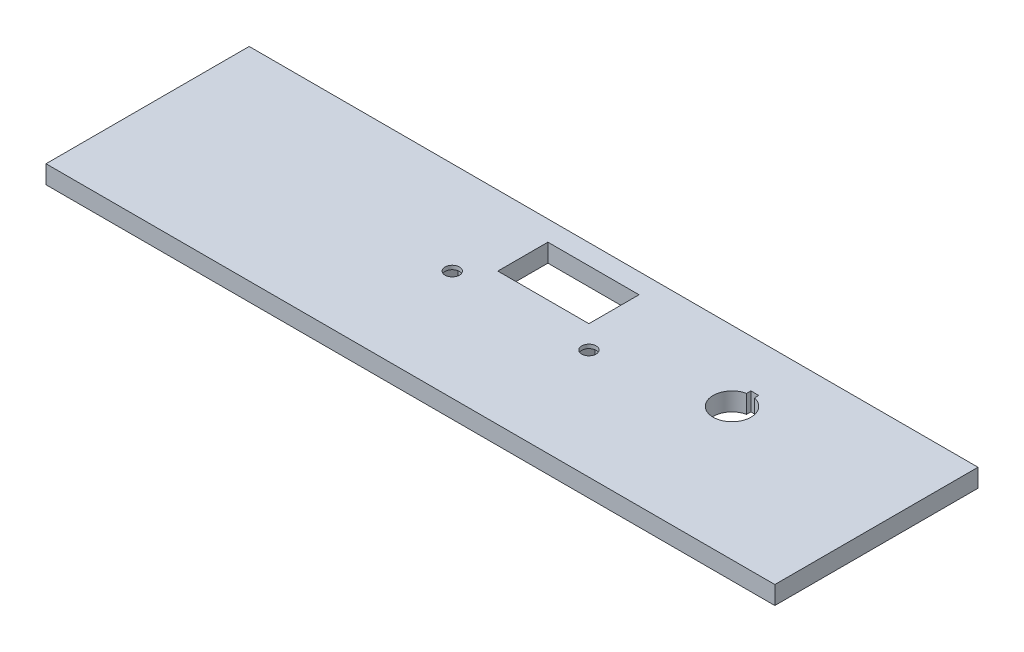
SolidWorks part; units mm, degrees
ref_plane "Front" through (0, 0, 0) normal (0, 0, 1) x (1, 0, 0)
ref_plane "Top" through (0, 0, 0) normal (0, 1, 0) x (1, 0, 0)
ref_plane "Right" through (0, 0, 0) normal (1, 0, 0) x (0, 0, -1)
sketch "Sketch2" plane through (0, 0, 0) normal (0, 1, 0) x (1, 0, 0)
  line L0 (51.5038, 15.0954) -> (51.5038, 13.8965)
  line L1 (-101.6, 28.321) -> (101.6, 28.321)
  line L2 (-101.6, 28.321) -> (-101.6, -28.321)
  line L3 (-101.6, -28.321) -> (101.6, -28.321)
  line L4 (101.6, 28.321) -> (101.6, -28.321)
  line L5 (-101.6, 28.321) -> (101.6, -28.321) construction
  line L6 (-101.6, -28.321) -> (101.6, 28.321) construction
  line L7 (51.5038, 15.0954) -> (53.7034, 15.0954)
  line L8 (52.6036, 8.742) -> (52.6036, 14.0125) construction
  line L9 (53.7034, 15.0954) -> (53.7034, 13.8965)
  line L10 (0, -55) -> (0, 55) construction
  line L11 (-12.7, 22.712) -> (12.7, 22.712)
  line L12 (-12.7, 22.712) -> (-12.7, 8.742)
  line L13 (-12.7, 8.742) -> (12.7, 8.742)
  line L14 (12.7, 22.712) -> (12.7, 8.742)
  line L15 (-12.7, 22.712) -> (12.7, 8.742) construction
  line L16 (-12.7, 8.742) -> (12.7, 22.712) construction
  circle A0 centre (52.6036, 8.742) radius 5.2705
  circle A1 centre (-19.05, 2.392) radius 2
  circle A2 centre (19.05, 2.392) radius 2
  point P0 (0, 0)
  point P13 (52.6036, 15.0954)
  point P14 (0, 15.727)
  dimension "D1" = 10.541
  dimension "D8" = 4
  dimension "D2" = 1.1989
  dimension "D3" = 1.0998
  dimension "D4" = 25.4
  dimension "D5" = 13.97
  dimension "D6" = 203.2
  dimension "D7" = 56.642
  dimension "D9" = 6.35
  dimension "D10" = 19.05
extrude "Boss-Extrude1" add sketch "Sketch2" along normal blind 5.08 contours L4 L1 L2 L3 A0 L0 L7 L9
sketch "Sketch4" plane through (0, 0, 0) normal (0, -1, 0) x (1, 0, 0)
  line L0 (0, -2.794) -> (0, 2.794) construction
  line L1 (-16.7695, -6.342) -> (-14.4889, -2.392)
  line L2 (-14.4889, -2.392) -> (-16.7695, 1.558)
  line L3 (-16.7695, 1.558) -> (-21.3305, 1.558)
  line L4 (101.6, -28.321) -> (101.6, 28.321)
  line L5 (101.6, 28.321) -> (-101.6, 28.321)
  line L6 (-101.6, 28.321) -> (-101.6, -28.321)
  line L7 (-101.6, -28.321) -> (101.6, -28.321)
  line L8 (101.6, -28.321) -> (101.6, 28.321)
  line L9 (101.6, 28.321) -> (-101.6, 28.321)
  line L10 (-101.6, 28.321) -> (-101.6, -28.321)
  line L11 (-101.6, -28.321) -> (101.6, -28.321)
  line L12 (-21.3305, 1.558) -> (-23.6111, -2.392)
  line L13 (-23.6111, -2.392) -> (-21.3305, -6.342)
  line L14 (-21.3305, -6.342) -> (-16.7695, -6.342)
  line L15 (16.7695, -6.342) -> (14.4889, -2.392)
  line L16 (21.3305, -6.342) -> (16.7695, -6.342)
  line L17 (23.6111, -2.392) -> (21.3305, -6.342)
  line L18 (21.3305, 1.558) -> (23.6111, -2.392)
  line L19 (16.7695, 1.558) -> (21.3305, 1.558)
  line L20 (14.4889, -2.392) -> (16.7695, 1.558)
  line L21 (101.6, 28.321) -> (101.6, -28.321)
  line L22 (-101.6, -28.321) -> (-101.6, 28.321)
  circle A0 centre (19.05, -2.392) radius 2 construction
  circle A1 centre (-19.05, -2.392) radius 2 construction
  circle A2 centre (19.05, -2.392) radius 2
  circle A3 centre (-19.05, -2.392) radius 2
  circle A4 centre (-19.05, -2.392) radius 3.95 construction
  dimension "D2" = 7.9
  dimension "D1" = 0
extrude "Cut-Extrude1" cut sketch "Sketch4" against normal blind 4 contours L2 L3 L12 L13 L14 L1 | L20 L19 L18 L17 L16 L15
sketch "Sketch5" plane through (0, 0, 28.321) normal (0, 0, 1) x (1, 0, 0)
  line L0 (0, -2.794) -> (0, 2.794) construction
  line L1 (-66.675, 5.08) -> (-60.325, 5.08)
  line L2 (-66.675, 5.08) -> (-66.675, -7.62)
  line L3 (-66.675, -7.62) -> (-60.325, -7.62)
  line L4 (-60.325, 5.08) -> (-60.325, -7.62)
  line L5 (66.675, -7.62) -> (60.325, -7.62)
  line L6 (60.325, 5.08) -> (60.325, -7.62)
  line L7 (66.675, 5.08) -> (60.325, 5.08)
  line L8 (-101.6, 0) -> (101.6, 0)
  line L9 (101.6, 0) -> (101.6, 5.08)
  line L10 (101.6, 5.08) -> (-101.6, 5.08)
  line L11 (-101.6, 5.08) -> (-101.6, 0)
  line L12 (-101.6, 0) -> (101.6, 0)
  line L13 (101.6, 0) -> (101.6, 5.08)
  line L14 (101.6, 5.08) -> (-101.6, 5.08)
  line L15 (-101.6, 5.08) -> (-101.6, 0)
  line L16 (66.675, 5.08) -> (66.675, -7.62)
  circle A0 centre (-63.5, -3.81) radius 1.5
  circle A1 centre (63.5, -3.81) radius 1.5
  point P18 (-63.5, -7.62)
  line M13 (-101.6, 0) -> (101.6, 0)
  line M15 (101.6, 5.08) -> (-101.6, 5.08)
  dimension "D4" = 3
  dimension "D2" = 6.35
  dimension "D3" = 12.7
  dimension "D5" = 3.81
  dimension "D6" = 63.5
  dimension "D1" = 0
extrude "Boss-Extrude2" add sketch "Sketch5" along normal blind 3.81 from surface at -56.642 contours L4 L2 L3 A0 M13 | L4 L2 M15 M13 | L16 L6 M15 M13 | L16 L6 L5 A1 M13
